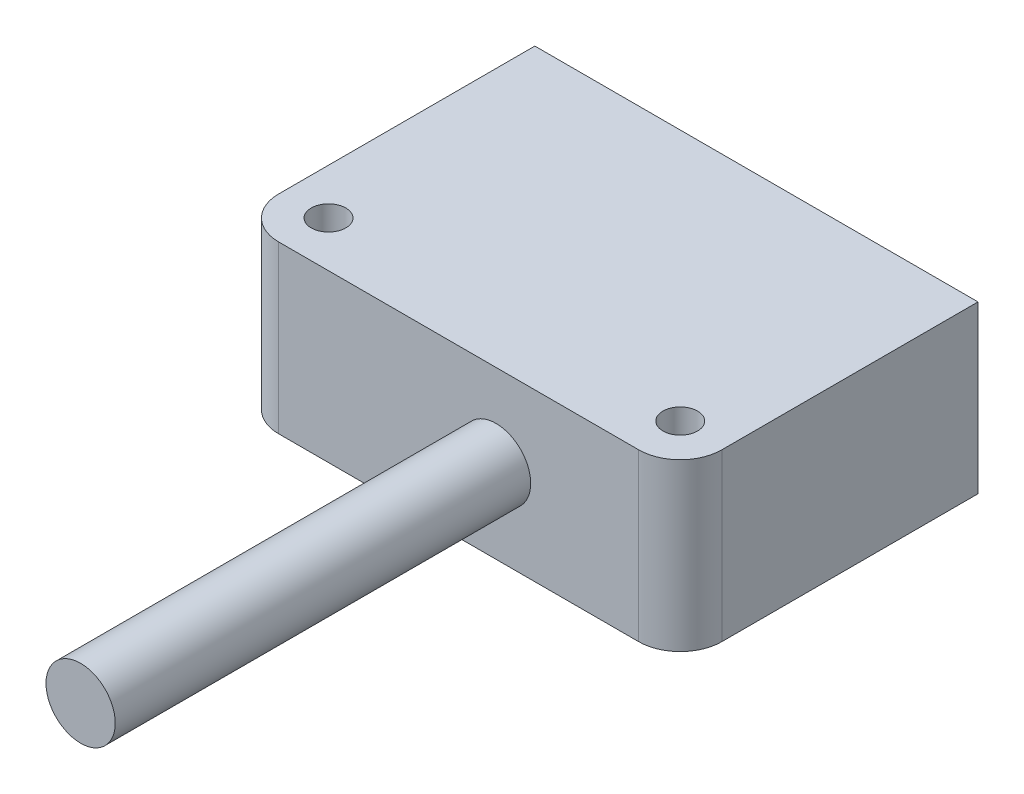
SolidWorks part; units mm, degrees
material "ABS 塑料颗粒"
ref_plane "前视基准面" through (0, 0, 0) normal (0, 0, 1) x (1, 0, 0)
ref_plane "上视基准面" through (0, 0, 0) normal (0, 1, 0) x (1, 0, 0)
ref_plane "右视基准面" through (0, 0, 0) normal (1, 0, 0) x (0, 0, -1)
other "Configuration Table"
sketch "草图1" plane through (0, 0, 0) normal (0, 1, 0) x (1, 0, 0)
  line L0 (0, 0) -> (0, -7.45) construction
  line L1 (-16, -10.75) -> (16, -10.75)
  line L2 (-16, -10.75) -> (-16, 10.75)
  line L3 (-16, 10.75) -> (16, 10.75)
  line L4 (16, -10.75) -> (16, 10.75)
  line L5 (-16, -10.75) -> (16, 10.75) construction
  line L6 (-16, 10.75) -> (16, -10.75) construction
  line L7 (-12.7, -7.45) -> (12.7, -7.45) construction
  line L8 (-12.7, -7.45) -> (-12.7, -10.75) construction
  line L9 (-12.7, -7.45) -> (-16, -7.45) construction
  circle A0 centre (-12.7, -7.45) radius 1.5 construction
  point P0 (0, 0)
  point P11 (0, -7.45)
  dimension "D4" = 3
  dimension "D1" = 21.5
  dimension "D2" = 32
  dimension "D3" = 25.4
extrude "凸台-拉伸1" add sketch "草图1" along normal blind 12
hole_wizard "M3 螺纹孔1" positions "草图2" profile "草图3" tap size "M3" standard "GB" end condition through all
sketch "草图2" plane through (0, 12, 0) normal (0, 1, 0) x (1, 0, 0)
  point P0 (-12.7, -7.45)
  point P3 (12.7, -7.45)
sketch "草图3" plane through (-12.7, 12, 7.45) normal (1, 0, 0) x (0, 0, 1)
  line L0 (0, 0) -> (0, 12)
  line L1 (0, 12) -> (1.25, 12)
  line L2 (1.25, 12) -> (1.25, 0)
  line L5 (1.25, 0) -> (0, 0)
  line L11 (0, -6.35) -> (0, 107.95) construction
  dimension "通孔螺纹孔钻头直径" = 2.5
  dimension "通孔螺纹孔钻头深度" = 12
cosmetic thread "孔螺纹线1" parameters "D2"=3
cosmetic thread "孔螺纹线2" parameters "D2"=3
fillet "圆角1" radius 3 2 edges at (16, 6, 10.75) (-16, 6, 10.75)
sketch "草图4" plane through (0, 0, 10.75) normal (0, 0, 1) x (1, 0, 0)
  line L0 (16, 6) -> (-16, 6) construction
  line L1 (16, 12) -> (16, 0) construction
  line L2 (-16, 0) -> (-16, 12) construction
  circle A0 centre (2.7, 6) radius 2.5
  dimension "D1" = 5
  dimension "D2" = 13.3
extrude "凸台-拉伸2" add sketch "草图4" along normal blind 30
